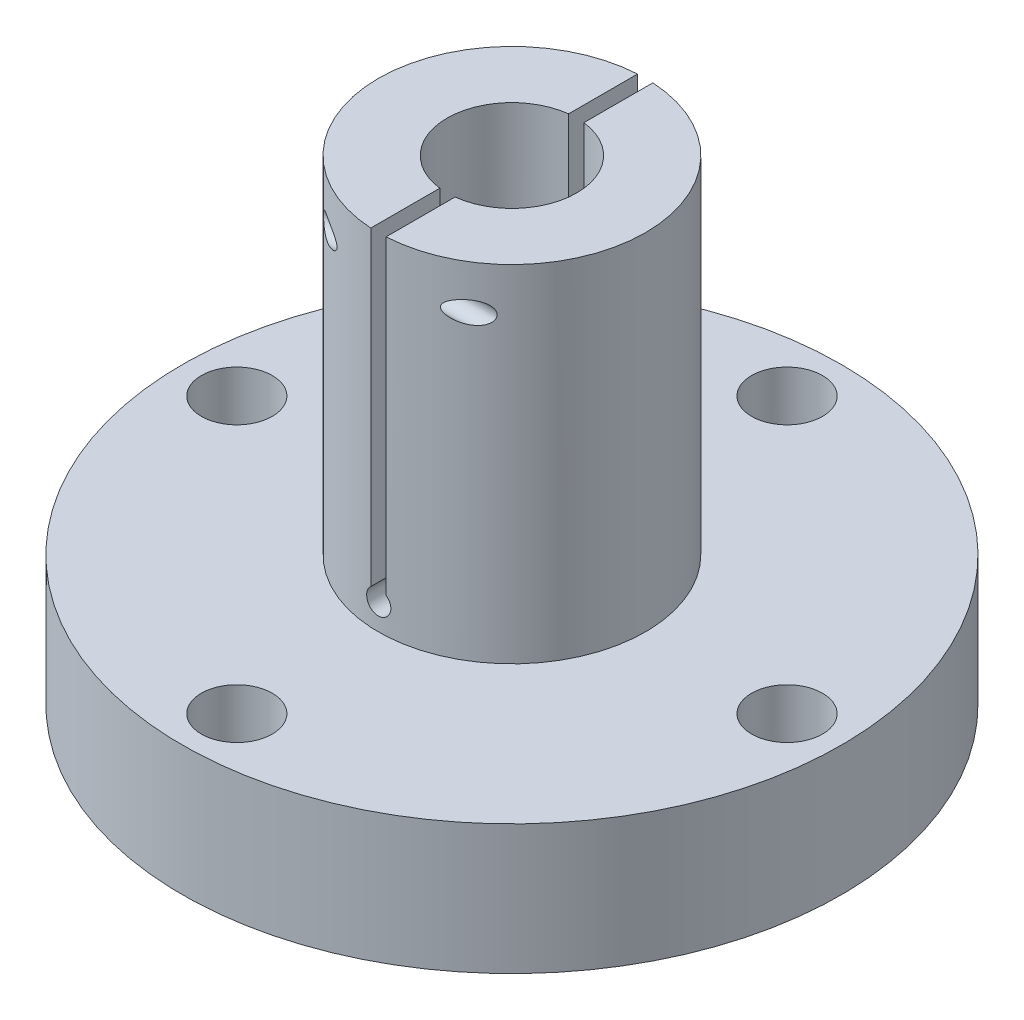
SolidWorks part; units mm, degrees
material "AISI 1045 Steel, cold drawn"
ref_plane "Front Plane" through (0, 0, 0) normal (0, 0, 1) x (1, 0, 0)
ref_plane "Top Plane" through (0, 0, 0) normal (0, 1, 0) x (1, 0, 0)
ref_plane "Right Plane" through (0, 0, 0) normal (1, 0, 0) x (0, 0, -1)
sketch "Sketch1" plane through (0, 0, 0) normal (0, 0, 1) x (1, 0, 0)
  line L0 (0, 0) -> (0, 66.6298) construction
  line L1 (7.5, 61.8681) -> (15.454, 61.8681)
  line L2 (15.454, 61.8681) -> (15.454, 21.8681)
  line L3 (15.454, 21.8681) -> (38.1235, 21.8681)
  line L4 (38.1235, 21.8681) -> (38.1235, 6.8681)
  line L5 (38.1235, 6.8681) -> (25, 6.8681)
  line L6 (25, 6.8681) -> (25, 13.8681)
  line L7 (25, 13.8681) -> (9, 13.8681)
  line L8 (9, 13.8681) -> (9, 21.8681)
  line L9 (9, 21.8681) -> (7.5, 21.8681)
  line L10 (7.5, 61.8681) -> (7.5, 21.8681)
  dimension "D1" = 40
  dimension "D2" = 7
  dimension "D3" = 15
  dimension "D4" = 50
  dimension "D5" = 18
  dimension "D6" = 15
revolve "Revolve1" add sketch "Sketch1" angle 360 about L0
sketch "Sketch2" plane through (0, 0, 0) normal (0, 0, 1) x (1, 0, 0)
  line L0 (38.1235, 21.8681) -> (-38.1235, 21.8681) construction
  line L1 (-0.8974, 116.9817) -> (0.8716, 116.9817)
  line L2 (-0.8974, 116.9817) -> (-0.8974, 25.9533)
  line L4 (0.8716, 116.9817) -> (0.8716, 25.9533)
  line L5 (-0.8974, 116.9817) -> (0.8716, 25.9533) construction
  line L6 (-0.8441, 26.0825) -> (0.8716, 116.9817) construction
  arc A0 (-0.8974, 25.9533) -> (0.8716, 25.9533) centre (-0.0129, 24.8681) ccw
  point P0 (0, 70.8034)
  dimension "D1" = 1.4
  dimension "D2" = 3
extrude "Cut-Extrude1" cut sketch "Sketch2" against normal mid plane 40
ref_plane "Plane1" through (20, 0, 0) normal (1, 0, 0) x (0, 0, -1)
sketch "Sketch3" plane through (20, 0, 0) normal (1, 0, 0) x (0, 0, -1)
  line L0 (0, 0) -> (0, 78.3067) construction
  circle A0 centre (-13, 56.8059) radius 1.25
  circle A1 centre (13, 56.8059) radius 1.25
  dimension "D3" = 2.5
  dimension "D4" = 2.5
  dimension "D1" = 13
  dimension "D2" = 13
extrude "Cut-Extrude2" cut sketch "Sketch3" against normal blind 17
sketch "Sketch4" plane through (3, 0, 0) normal (1, 0, 0) x (0, 0, -1)
  circle A0 centre (13, 56.8059) radius 0.5028
  circle A1 centre (-13, 56.8059) radius 0.5026
extrude "Cut-Extrude3" cut sketch "Sketch4" against normal blind 3
mirror "Mirror1" about plane through (0, 0, 0) normal (1, 0, 0) of "Cut-Extrude3", "Cut-Extrude2"
sketch "Sketch5" plane through (0, 6.8681, 0) normal (0, -1, 0) x (1, 0, 0)
  circle A0 centre (31.8252, 0) radius 2.25
  circle A1 centre (0, -31.8252) radius 2.25
  circle A2 centre (-31.8252, 0) radius 2.25
  circle A3 centre (0, 31.8252) radius 2.25
  point P11 (0, 0)
  dimension "D1" = 4.5
  dimension "D2" = 4
extrude "Cut-Extrude4" cut sketch "Sketch5" against normal blind 6
sketch "Sketch6" plane through (0, 12.8681, 0) normal (0, -1, 0) x (1, 0, 0)
  circle A0 centre (0, 31.8252) radius 4.1
  circle A1 centre (31.8252, 0) radius 4.1
  circle A2 centre (0, -31.8252) radius 4.1
  circle A3 centre (-31.8252, 0) radius 4.1
  point P12 (0, 0)
  dimension "D1" = 8.2
  dimension "D2" = 4
extrude "Cut-Extrude5" cut sketch "Sketch6" against normal blind 26
